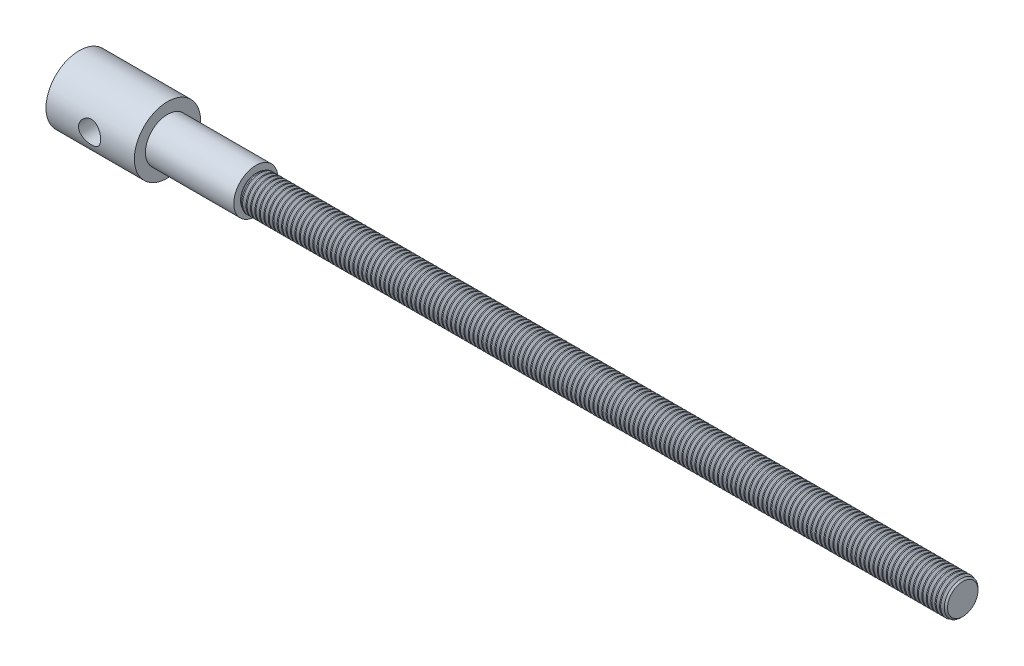
SolidWorks part; units mm, degrees
revolve "BaseBody" add sketch "BodySke" angle 360 about L14
sketch "BodySke" plane through (0, 0, 0) normal (0, 0, 1) x (1, 0, 0)
  line L0 (306.203, 15.875) -> (306.203, -6.35) construction
  line L1 (2, 15.875) -> (2, -3.175) construction
  line L2 (320, 6.35) -> (320, 3.175) construction
  line L10 (0, 8) -> (320, 8)
  line L12 (320, 8) -> (320, 0)
  line L13 (320, 0) -> (0, 0)
  line L14 (-3.175, 0) -> (107.95, 0) construction
  line L18 (0, 8) -> (0, 0)
  dimension "Diameter" = 16
  dimension "Length" = 320
  dimension "Advance" = 2
  dimension "Minor_dia" = 13.797
  dimension "Thread_max" = 320
cosmetic thread "ThreadCosmetic" [suppressed] parameters "Thread_minor"=13.797
ref_plane "Plane1" through (0, 0, 0) normal (0, 0, 1) x (1, 0, 0)
ref_plane "Plane2" through (0, 0, 0) normal (0, 1, 0) x (1, 0, 0)
ref_plane "Plane3" through (0, 0, 0) normal (1, 0, 0) x (0, 0, -1)
chamfer "Chamfer1" distance 1.1015 angle 45 2 edges at (0, 0, 8) (320, 0, 8)
sketch "ThdSchSke" plane through (0, 0, 0) normal (0, 0, 1) x (1, 0, 0)
  line L0 (0.7713, -6.8985) -> (0, -8)
  line L1 (0.7713, -6.8985) -> (1.5426, -8)
  line L2 (1.5426, -8) -> (1.5426, -10)
  line L3 (-3.175, 0) -> (5.1513, 0) construction
  line L4 (0, 8) -> (0, -8) construction
  line L5 (1.5426, -10) -> (0, -10)
  line L6 (0, -10) -> (0, -8)
  dimension "Thread_minor" = 13.797
  dimension "Diameter" = 16
revolve "ThreadSchematic" cut sketch "ThdSchSke" angle 360 about L3
pattern_linear "ThdSchPat" count 159 spacing 2.0126 along (1, 0, 0) of "ThreadSchematic"
sketch "Çizim1" plane through (0, 0, 0) normal (-1, 0, 0) x (0, 0, 1)
  circle A0 centre (0, 0) radius 10
extrude "Yükseklik-Ekstrüzyon1" add sketch "Çizim1" along normal blind 40
sketch "Çizim2" plane through (-40, 0, 0) normal (-1, 0, 0) x (0, 0, 1)
  circle A0 centre (0, 0) radius 15
extrude "Yükseklik-Ekstrüzyon2" add sketch "Çizim2" along normal blind 40
sketch "Çizim3" plane through (0, 0, 0) normal (0, 0, 1) x (1, 0, 0)
  circle A1 centre (-60.2789, 0) radius 5
extrude "Kes-Ekstrüzyon1" cut sketch "Çizim3" against normal mid plane 40
equation "\"Thread_minor@ThreadCosmetic\" = \"Minor_dia@BodySke\""
equation "\"Chamfer@Chamfer1\" =  ( \"Diameter@BodySke\" - \"Minor_dia@BodySke\" ) / 2"
equation "\"Thread_minor@ThdSchSke\" = \"Minor_dia@BodySke\""
equation "\"Diameter@ThdSchSke\" = \"Diameter@BodySke\""
equation "\"Overcut@ThdSchSke\" = \"Diameter@BodySke\" * 1.25"
equation "\"Num_threads@ThdSchPat\" = int( (\"Thread_max@BodySke\" - \"Advance@BodySke\" ) / \"Advance@BodySke\" + 0.999 ) + 1"
equation "\"Advance@ThdSchPat\" = \"Thread_max@BodySke\" /  ( \"Num_threads@ThdSchPat\" - 1 ) 'relax it"
equation "\"Num_threads@ThdSchPat\" = \"Num_threads@ThdSchPat\" - sgn( \"Num_threads@ThdSchPat\" - 1 ) '---chamfered tips only---"
